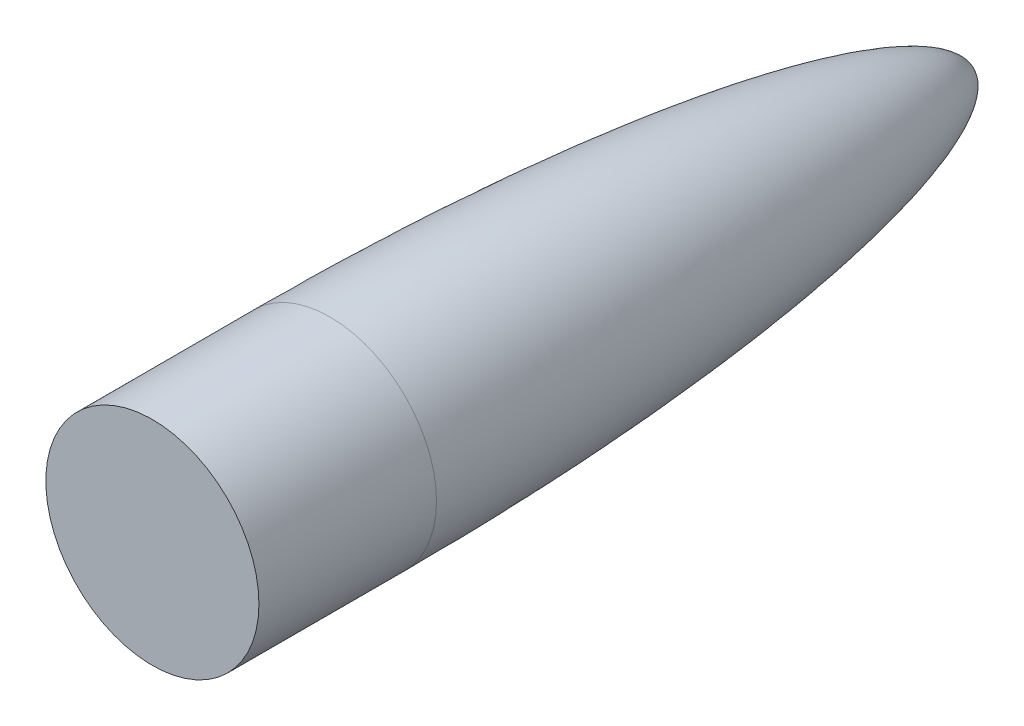
SolidWorks part; units mm, degrees
ref_plane "Front Plane" through (0, 0, 0) normal (0, 0, 1) x (1, 0, 0)
ref_plane "Top Plane" through (0, 0, 0) normal (0, 1, 0) x (1, 0, 0)
ref_plane "Right Plane" through (0, 0, 0) normal (1, 0, 0) x (0, 0, -1)
sketch "Sketch1" plane through (0, 0, 0) normal (1, 0, 0) x (0, 0, -1)
  line L0 (0, 76.2) -> (0, 0)
  line L1 (0, 0) -> (457.2, 0)
  spline S0 degree 4 poles (-45.7212, 75.818) (-45.5436, 75.821) (-45.1859, 75.827) (-44.4536, 75.8388) (-43.0745, 75.8618) (-40.2991, 75.9034) (-36.5333, 75.9595) (-31.3026, 76.0222) (-24.5017, 76.0967) (-16.8071, 76.1514) (-10.4957, 76.1861) (-2.5895, 76.2003) (1.399, 76.2011) (6.722, 76.1936) (10.8243, 76.1797) (15.3251, 76.1589) (19.6131, 76.1311) (24.021, 76.0963) (28.3629, 76.0546) (33.8296, 75.9937) (40.3701, 75.9067) (50.1927, 75.7497) (63.2821, 75.4841) (78.555, 75.091) (93.8226, 74.5965) (106.9079, 74.0986) (117.8094, 73.6332) (126.5297, 73.2303) (137.4279, 72.6877) (150.5026, 71.9732) (165.7509, 71.0446) (183.1688, 69.8473) (200.5763, 68.5073) (217.9716, 67.0164) (235.3524, 65.3648) (252.7159, 63.5406) (270.0589, 61.5296) (287.3769, 59.3136) (308.9866, 56.2601) (334.842, 52.0843) (363.1481, 46.6366) (391.1648, 39.8262) (413.1662, 32.9594) (428.332, 26.8879) (437.961, 22.0574) (444.2769, 18.1347) (448.4811, 14.9275) (451.3625, 12.2396) (453.3709, 9.9391) (454.795, 7.9044) (455.8005, 6.0605) (456.4726, 4.413) (456.9556, 2.7152) (457.1501, 1.4237) (457.2, 0.5345) (457.2, 0) knots 0 0 0 0 0 0.001374 0.002747 0.005495 0.010989 0.021979 0.032968 0.043958 0.065937 0.076926 0.087916 0.096308 0.104701 0.113093 0.121486 0.129878 0.138271 0.146663 0.155056 0.171841 0.188626 0.222196 0.255767 0.289337 0.306122 0.322907 0.339692 0.356477 0.390047 0.423618 0.457188 0.490758 0.524328 0.557898 0.591469 0.625039 0.658609 0.692179 0.75932 0.82646 0.88025 0.91382 0.936432 0.951974 0.963004 0.970923 0.977039 0.982232 0.986451 0.989986 0.993161 0.995889 1 1 1 1 1 construction
  spline S1 degree 4 poles (0, 76.2) (0.9952, 76.2) (3.0164, 76.1988) (6.722, 76.1936) (10.8243, 76.1797) (15.3251, 76.1589) (19.6131, 76.1311) (24.021, 76.0963) (28.3629, 76.0546) (33.8296, 75.9937) (40.3701, 75.9067) (50.1927, 75.7497) (63.2821, 75.4841) (78.555, 75.091) (93.8226, 74.5965) (106.9079, 74.0986) (117.8094, 73.6332) (126.5297, 73.2303) (137.4279, 72.6877) (150.5026, 71.9732) (165.7509, 71.0446) (183.1688, 69.8473) (200.5763, 68.5073) (217.9716, 67.0164) (235.3524, 65.3648) (252.7159, 63.5406) (270.0589, 61.5296) (287.3769, 59.3136) (308.9866, 56.2601) (334.842, 52.0843) (363.1481, 46.6366) (391.1648, 39.8262) (413.1662, 32.9594) (428.332, 26.8879) (437.961, 22.0574) (444.2769, 18.1347) (448.4811, 14.9275) (451.3625, 12.2396) (453.3709, 9.9391) (454.795, 7.9044) (455.8005, 6.0605) (456.4726, 4.413) (456.9556, 2.7152) (457.1501, 1.4237) (457.2, 0.5345) (457.2, 0) knots 0.087916 0.087916 0.087916 0.087916 0.087916 0.096308 0.104701 0.113093 0.121486 0.129878 0.138271 0.146663 0.155056 0.171841 0.188626 0.222196 0.255767 0.289337 0.306122 0.322907 0.339692 0.356477 0.390047 0.423618 0.457188 0.490758 0.524328 0.557898 0.591469 0.625039 0.658609 0.692179 0.75932 0.82646 0.88025 0.91382 0.936432 0.951974 0.963004 0.970923 0.977039 0.982232 0.986451 0.989986 0.993161 0.995889 1 1 1 1 1
ref_axis "Axis1" through (0, 0, -480.06) along (0, 0, 1)
revolve "Revolve1" add sketch "Sketch1" angle 360 about axis through (0, 0, -480.06) along (0, 0, 1)
sketch "Sketch2" plane through (0, 0, 0) normal (0, 0, 1) x (1, 0, 0)
  circle A0 centre (0, 0) radius 76.2
  dimension "D1" = 152.4
extrude "Boss-Extrude1" add sketch "Sketch2" along normal blind 127
equation "\"BodyTubeRadius\"= 3in"
equation "\"ratio\"= 3"
equation "\"NoseConeLength\"= \"ratio\" * 2 * \"BodyTubeRadius\""
equation "\"D1@Sketch2\"=2*\"BodyTubeRadius\""
equation "\"BodyTubeLength\"=5"
